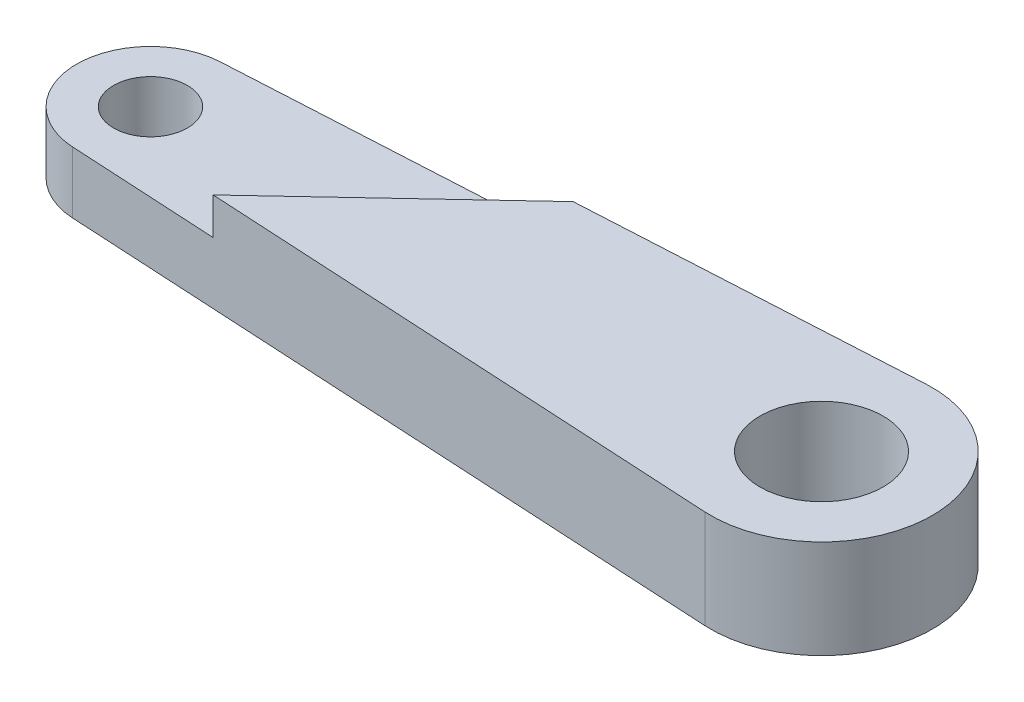
SolidWorks part; units mm, degrees
ref_plane "前视基准面" through (0, 0, 0) normal (0, 0, 1) x (1, 0, 0)
ref_plane "上视基准面" through (0, 0, 0) normal (0, 1, 0) x (1, 0, 0)
ref_plane "右视基准面" through (0, 0, 0) normal (1, 0, 0) x (0, 0, -1)
sketch "草图1" plane through (0, 0, 0) normal (0, 1, 0) x (1, 0, 0)
  line L0 (0, 0) -> (54.5, 0) construction
  line L1 (-0.3303, 5.9909) -> (54.0046, 8.9864)
  line L2 (-0.3303, -5.9909) -> (54.0046, -8.9864)
  circle A0 centre (0, 0) radius 3
  circle A1 centre (0, 0) radius 6
  circle A2 centre (54.5, 0) radius 9
  circle A3 centre (54.5, 0) radius 5
  dimension "D1" = 6
  dimension "D2" = 12
  dimension "D4" = 18
  dimension "D5" = 10
  dimension "D3" = 54.5
extrude "凸台-拉伸1" add sketch "草图1" along normal mid plane 8
sketch "草图2" plane through (0, 4, 0) normal (0, 1, 0) x (1, 0, 0)
  line L0 (26.8372, 7.4886) -> (11.7502, -6.6569)
  line L1 (-0.3303, 5.9909) -> (54.0046, 8.9864) construction
  line L2 (-0.3303, -5.9909) -> (54.0046, -8.9864) construction
  line L3 (11.7502, -6.6569) -> (-12.8595, -6.6569)
  line L4 (-12.8595, -6.6569) -> (-12.8595, 10.7334)
  line L5 (-12.8595, 10.7334) -> (26.8372, 7.4886)
  dimension "D1" = 40
extrude "切除-拉伸1" cut sketch "草图2" against normal blind 3
